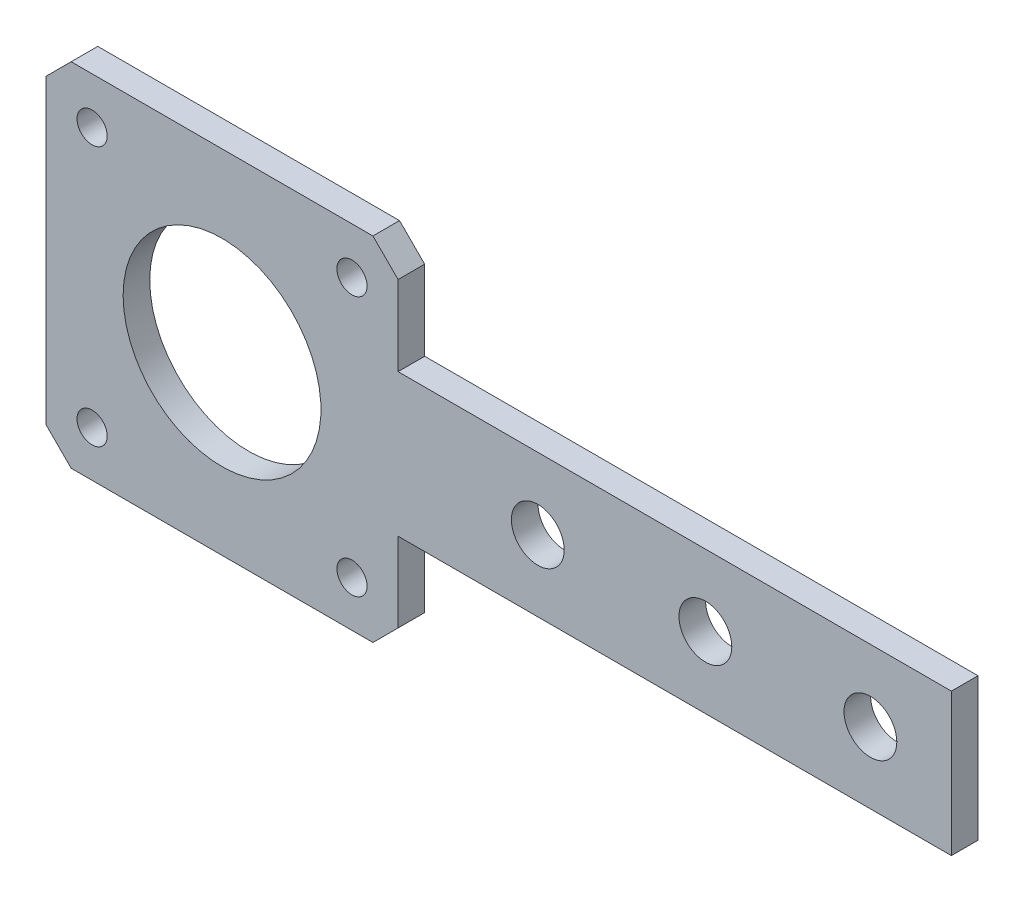
SolidWorks part; units mm, degrees
material "5052-H32"
ref_plane "Front Plane" through (0, 0, 0) normal (0, 0, 1) x (1, 0, 0)
ref_plane "Top Plane" through (0, 0, 0) normal (0, 1, 0) x (1, 0, 0)
ref_plane "Right Plane" through (0, 0, 0) normal (1, 0, 0) x (0, 0, -1)
sketch "Sketch1" plane through (0, 0, 0) normal (0, 0, 1) x (1, 0, 0)
  line L12 (-1010.5863, 1449.0284) -> (-1010.5863, 1458.5112)
  line L13 (-1013.5863, 1446.0284) -> (-1010.5863, 1449.0284)
  line L14 (-1049.5863, 1446.0284) -> (-1013.5863, 1446.0284)
  line L15 (-1052.5863, 1449.0284) -> (-1049.5863, 1446.0284)
  line L16 (-1052.5863, 1485.0284) -> (-1052.5863, 1449.0284)
  line L17 (-1049.5863, 1488.0284) -> (-1052.5863, 1485.0284)
  line L18 (-1013.5863, 1488.0284) -> (-1049.5863, 1488.0284)
  line L19 (-1010.5863, 1485.0284) -> (-1013.5863, 1488.0284)
  line L20 (-1010.5863, 1475.5112) -> (-1010.5863, 1485.0284)
  line L21 (-944.5812, 1475.5112) -> (-1010.5863, 1475.5112)
  line L22 (-944.5812, 1458.5112) -> (-944.5812, 1475.5112)
  line L23 (-1010.5863, 1458.5112) -> (-944.5812, 1458.5112)
extrude "Boss-Extrude1" add sketch "Sketch1" along normal blind 3.175
sketch "Sketch3" plane through (0, 0, 0) normal (0, 0, -1) x (-1, 0, 0)
  circle A1 centre (1031.5863, 1466.9941) radius 11.8
  circle A3 centre (1047.0863, 1482.4941) radius 1.8
  circle A5 centre (1047.0863, 1451.4941) radius 1.8
  circle A7 centre (1016.0863, 1451.4941) radius 1.8
  circle A9 centre (1016.0863, 1482.4941) radius 1.8
extrude "Cut-Extrude1" cut sketch "Sketch3" against normal through all
sketch "Sketch4" plane through (0, 0, 3.175) normal (0, 0, 1) x (1, 0, 0)
  line L0 (-993.9183, 1466.9903) -> (-947.1295, 1466.9903) construction
  line L1 (-1076.5914, 1466.9812) -> (-1001.3863, 1466.9983) construction
  circle A1 centre (-973.9272, 1466.9862) radius 3.15
  circle A2 centre (-993.9183, 1466.9903) radius 3.15
  circle A3 centre (-954.2414, 1466.9903) radius 3.15
extrude "Cut-Extrude2" cut sketch "Sketch4" against normal through all
